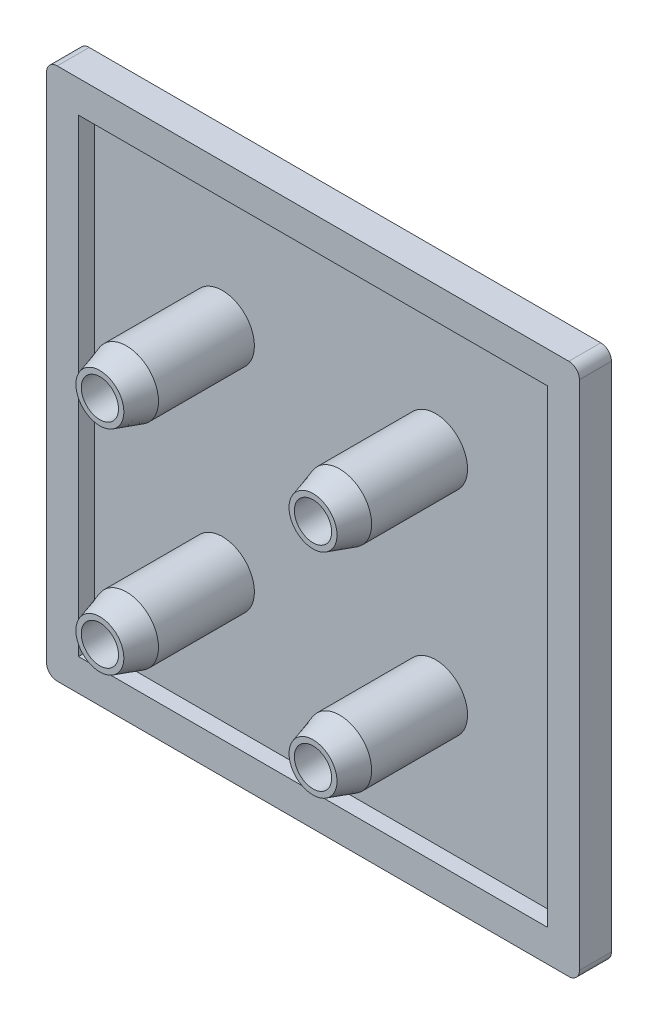
SolidWorks part; units mm, degrees
ref_plane "Front Plane" through (0, 0, 0) normal (0, 0, 1) x (1, 0, 0)
ref_plane "Top Plane" through (0, 0, 0) normal (0, 1, 0) x (1, 0, 0)
ref_plane "Right Plane" through (0, 0, 0) normal (1, 0, 0) x (0, 0, -1)
ref_plane "Plane1" through (0, 0, 0) normal (0, 0, 1) x (1, 0, 0)
sketch "Sketch1" plane through (0, 0, 0) normal (0, 0, 1) x (1, 0, 0)
  line L0 (-25, 24) -> (-25, -24)
  line L1 (-24, -25) -> (24, -25)
  line L2 (25, -24) -> (25, 24)
  line L3 (24, 25) -> (-24, 25)
  arc A0 (-25, -24) -> (-24, -25) centre (-24, -24) ccw
  arc A1 (24, -25) -> (25, -24) centre (24, -24) ccw
  arc A2 (25, 24) -> (24, 25) centre (24, 24) ccw
  arc A3 (-24, 25) -> (-25, 24) centre (-24, 24) ccw
extrude "Boss-Extrude1" add sketch "Sketch1" against normal blind 3
ref_plane "Plane2" through (0, 0, 0) normal (0, 0, 1) x (1, 0, 0)
sketch "Sketch2" plane through (0, 0, 0) normal (0, 0, 1) x (1, 0, 0)
  line L0 (-22, -22) -> (22, -22)
  line L1 (22, -22) -> (22, 22)
  line L2 (22, 22) -> (-22, 22)
  line L3 (-22, 22) -> (-22, -22)
extrude "Cut-Extrude1" cut sketch "Sketch2" against normal blind 1.5
ref_plane "Plane3" through (-10, 0, 0) normal (1, 0, 0) x (0, 0, -1)
sketch "Sketch3" plane through (-10, 0, 0) normal (1, 0, 0) x (0, 0, -1)
  line L0 (0, 10) -> (0, 11.75)
  line L1 (0, 11.75) -> (-10, 11.75)
  line L2 (-10, 11.75) -> (-10, 12.25)
  line L3 (-10, 12.25) -> (-7.5, 13)
  line L4 (-7.5, 13) -> (1.5, 13)
  line L5 (1.5, 13) -> (1.5, 10)
  line L6 (1.5, 10) -> (0, 10)
  line L7 (1.5, 10) -> (-10, 10) construction
revolve "Revolve1" add sketch "Sketch3" angle 360 about L7
ref_plane "Plane4" through (10, 0, 0) normal (1, 0, 0) x (0, 0, -1)
sketch "Sketch4" plane through (10, 0, 0) normal (1, 0, 0) x (0, 0, -1)
  line L0 (0, 10) -> (0, 11.75)
  line L1 (0, 11.75) -> (-10, 11.75)
  line L2 (-10, 11.75) -> (-10, 12.25)
  line L3 (-10, 12.25) -> (-7.5, 13)
  line L4 (-7.5, 13) -> (1.5, 13)
  line L5 (1.5, 13) -> (1.5, 10)
  line L6 (1.5, 10) -> (0, 10)
  line L7 (1.5, 10) -> (-10, 10) construction
revolve "Revolve2" add sketch "Sketch4" angle 360 about L7
ref_plane "Plane5" through (10, 0, 0) normal (1, 0, 0) x (0, 0, -1)
sketch "Sketch5" plane through (10, 0, 0) normal (1, 0, 0) x (0, 0, -1)
  line L0 (0, -10) -> (0, -8.25)
  line L1 (0, -8.25) -> (-10, -8.25)
  line L2 (-10, -8.25) -> (-10, -7.75)
  line L3 (-10, -7.75) -> (-7.5, -7)
  line L4 (-7.5, -7) -> (1.5, -7)
  line L5 (1.5, -7) -> (1.5, -10)
  line L6 (1.5, -10) -> (0, -10)
  line L7 (1.5, -10) -> (-10, -10) construction
revolve "Revolve3" add sketch "Sketch5" angle 360 about L7
ref_plane "Plane6" through (-10, 0, 0) normal (1, 0, 0) x (0, 0, -1)
sketch "Sketch6" plane through (-10, 0, 0) normal (1, 0, 0) x (0, 0, -1)
  line L0 (0, -10) -> (0, -8.25)
  line L1 (0, -8.25) -> (-10, -8.25)
  line L2 (-10, -8.25) -> (-10, -7.75)
  line L3 (-10, -7.75) -> (-7.5, -7)
  line L4 (-7.5, -7) -> (1.5, -7)
  line L5 (1.5, -7) -> (1.5, -10)
  line L6 (1.5, -10) -> (0, -10)
  line L7 (1.5, -10) -> (-10, -10) construction
revolve "Revolve4" add sketch "Sketch6" angle 360 about L7
